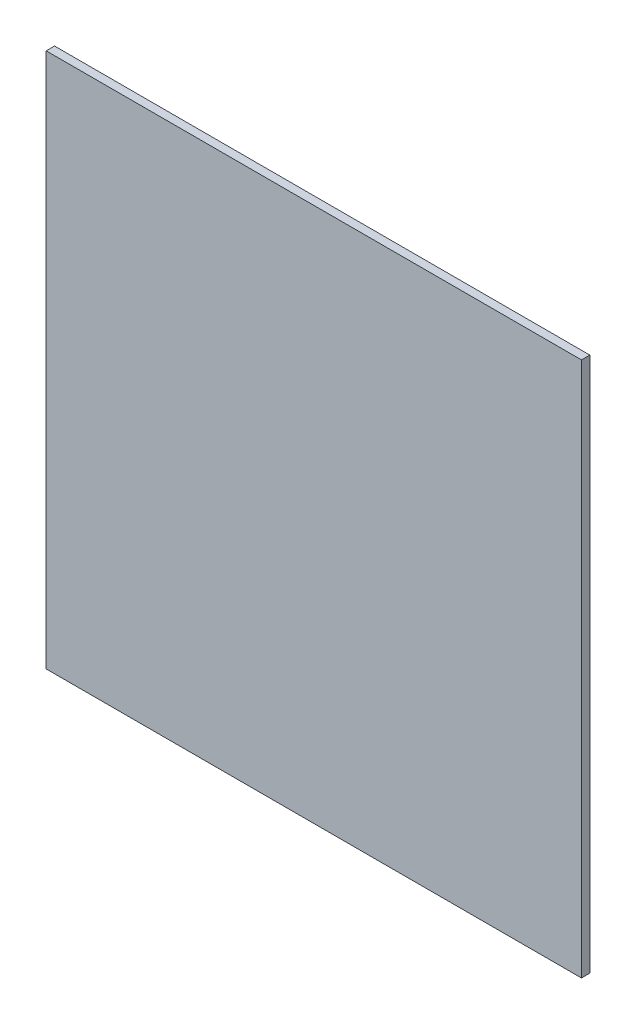
SolidWorks part; units mm, degrees
ref_plane "Front Plane" through (0, 0, 0) normal (0, 0, 1) x (1, 0, 0)
ref_plane "Top Plane" through (0, 0, 0) normal (0, 1, 0) x (1, 0, 0)
ref_plane "Right Plane" through (0, 0, 0) normal (1, 0, 0) x (0, 0, -1)
sketch "Sketch1" plane through (0, 0, 0) normal (0, 0, 1) x (1, 0, 0)
  line L1 (-609.6, 609.6) -> (609.6, 609.6)
  line L2 (-609.6, 609.6) -> (-609.6, -609.6)
  line L3 (-609.6, -609.6) -> (609.6, -609.6)
  line L4 (609.6, 609.6) -> (609.6, -609.6)
extrude "Boss-Extrude1" add sketch "Sketch1" along normal blind 19.05
